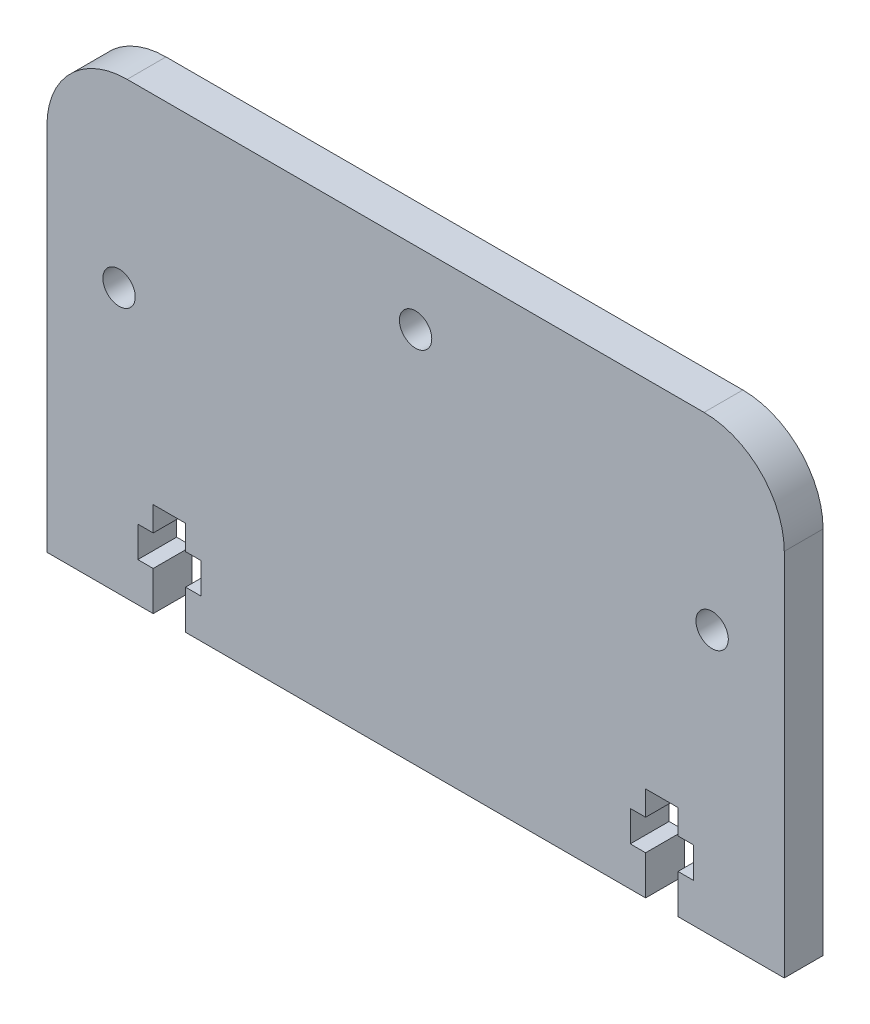
SolidWorks part; units mm, degrees
ref_plane "Front Plane" through (0, 0, 0) normal (0, 0, 1) x (1, 0, 0)
ref_plane "Top Plane" through (0, 0, 0) normal (0, 1, 0) x (1, 0, 0)
ref_plane "Right Plane" through (0, 0, 0) normal (1, 0, 0) x (0, 0, -1)
sketch "Sketch2" plane through (0, 0, 0) normal (0, 0, 1) x (1, 0, 0)
  line L0 (-56.975, 0) -> (56.975, 0)
  line L1 (-56.975, 0) -> (-56.975, 57.1)
  line L2 (56.975, 0) -> (56.975, 57.1)
  line L3 (-44.575, 69.5) -> (44.575, 69.5)
  arc A0 (-56.975, 57.1) -> (-44.575, 69.5) centre (-44.575, 57.1) cw
  arc A1 (44.575, 69.5) -> (56.975, 57.1) centre (44.575, 57.1) cw
  point P4 (0, 0)
  dimension "D2" = 12.4
  dimension "D1" = 113.95
  dimension "D3" = 69.5
extrude "Boss-Extrude1" add sketch "Sketch2" along normal blind 6
sketch "Sketch3" plane through (0, 0, 6) normal (0, 0, 1) x (1, 0, 0)
  line L0 (-40.55, 0) -> (-35.55, 0)
  line L1 (-56.975, 0) -> (56.975, 0) construction
  line L2 (-35.55, 0) -> (-35.55, 6.05)
  line L3 (-35.55, 6.05) -> (-33.175, 6.05)
  line L4 (-33.175, 6.05) -> (-33.175, 10.8)
  line L5 (-33.175, 10.8) -> (-35.55, 10.8)
  line L6 (-35.55, 10.8) -> (-35.55, 14.6)
  line L7 (-35.55, 14.6) -> (-40.55, 14.6)
  line L8 (-40.55, 14.6) -> (-40.55, 10.8)
  line L9 (-40.55, 10.8) -> (-42.925, 10.8)
  line L10 (-42.925, 10.8) -> (-42.925, 6.05)
  line L11 (-42.925, 6.05) -> (-40.55, 6.05)
  line L12 (-40.55, 6.05) -> (-40.55, 0)
  line L13 (0, 0) -> (0, 33.1398) construction
  dimension "D1" = 5
  dimension "D2" = 9.75
  dimension "D3" = 14.6
  dimension "D4" = 4.75
  dimension "D5" = 6.05
  dimension "D6" = 71.1
extrude "Cut-Extrude1" cut sketch "Sketch3" against normal through all
sketch "Sketch4" plane through (0, 0, 6) normal (0, 0, 1) x (1, 0, 0)
  line L0 (-56.975, 57.1) -> (-56.975, 0) construction
  line L2 (-56.975, 0) -> (-40.55, 0) construction
  circle A0 centre (-45.825, 41) radius 2.5
  dimension "D1" = 38.5
  dimension "D2" = 8.65
  dimension "D3" = 5
extrude "Hole1" cut sketch "Sketch4" against normal through all
sketch "Sketch5" plane through (0, 0, 6) normal (0, 0, 1) x (1, 0, 0)
  line L0 (44.575, 69.5) -> (-44.575, 69.5) construction
  line L2 (0, 0) -> (0, 58.3) construction
  circle A0 centre (0, 58.3) radius 2.5
  circle A1 centre (-45.825, 41) radius 2.5 construction
  dimension "D1" = 8.7
extrude "Hole2" cut sketch "Sketch5" against normal through all
mirror "Mirror1" about plane through (0, 0, 0) normal (1, 0, 0) of "Hole1", "Cut-Extrude1"
